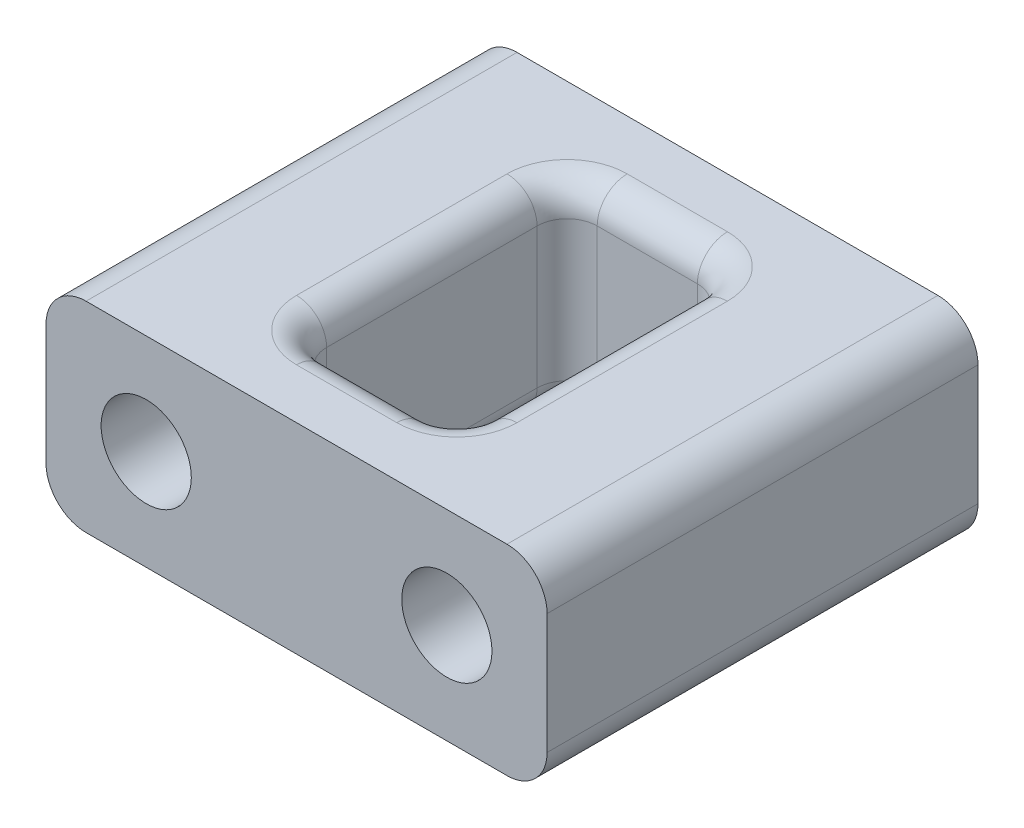
SolidWorks part; units mm, degrees
material "ABS"
ref_plane "前视基准面" through (0, 0, 0) normal (0, 0, 1) x (1, 0, 0)
ref_plane "上视基准面" through (0, 0, 0) normal (0, 1, 0) x (1, 0, 0)
ref_plane "右视基准面" through (0, 0, 0) normal (1, 0, 0) x (0, 0, -1)
sketch "草图1" plane through (0, 0, 0) normal (0, 0, 1) x (1, 0, 0)
  line L1 (0, 0) -> (25, 0)
  line L2 (0, 0) -> (0, 10)
  line L3 (0, 10) -> (25, 10)
  line L4 (25, 0) -> (25, 10)
  circle A0 centre (5, 5) radius 2.25
  circle A1 centre (20, 5) radius 2.25
  dimension "D2" = 15
  dimension "D3" = 4.5
  dimension "D4" = 4.5
  dimension "D5" = 5
  dimension "D6" = 5
  dimension "D8" = 5
  dimension "D1" = 25
  dimension "D7" = 10
extrude "凸台-拉伸1" add sketch "草图1" along normal blind 21.5
fillet "圆角1" radius 2 4 edges at (0, 0, 10.75) (0, 10, 10.75) (25, 0, 10.75) (25, 10, 10.75)
sketch "草图2" plane through (0, 10, 0) normal (0, 1, 0) x (1, 0, 0)
  line L0 (23, 0) -> (2, 0) construction
  line L1 (8.5, -4) -> (16.5, -4)
  line L2 (8.5, -4) -> (8.5, -17.5)
  line L3 (8.5, -17.5) -> (16.5, -17.5)
  line L4 (16.5, -4) -> (16.5, -17.5)
  line L5 (23, -21.5) -> (2, -21.5) construction
  line L6 (25, 0) -> (25, -21.5) construction
  line L7 (0, -21.5) -> (0, 0) construction
  dimension "D1" = 4
  dimension "D2" = 4
  dimension "D3" = 8.5
  dimension "D4" = 8.5
extrude "切除-拉伸1" cut sketch "草图2" against normal through all
fillet "圆角2" radius 1.5 12 edges at (8.5, 0, 10.75) (8.5, 10, 10.75) (12.5, 0, 17.5) (12.5, 10, 17.5) (12.5, 0, 4) (12.5, 10, 4) (16.5, 5, 17.5) (16.5, 0, 10.75) (16.5, 5, 4) (16.5, 10, 10.75) (8.5, 5, 4) (8.5, 5, 17.5)
